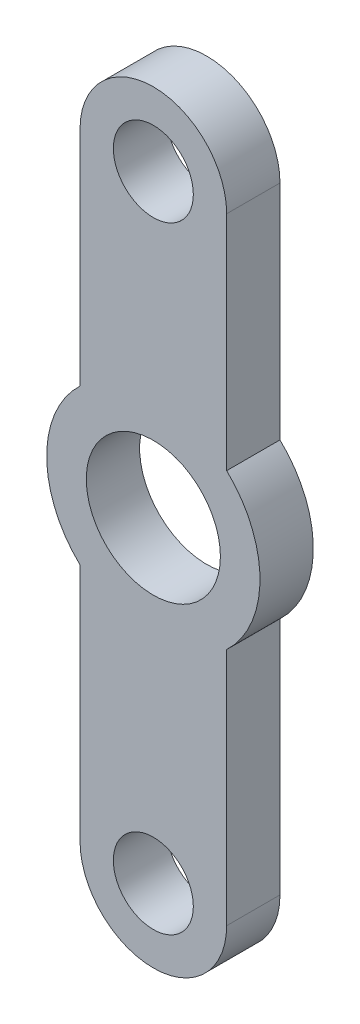
SolidWorks part; units mm, degrees
ref_plane "前视基准面" through (0, 0, 0) normal (0, 0, 1) x (1, 0, 0)
ref_plane "上视基准面" through (0, 0, 0) normal (0, 1, 0) x (1, 0, 0)
ref_plane "右视基准面" through (0, 0, 0) normal (1, 0, 0) x (0, 0, -1)
sketch "草图1" plane through (0, 0, 0) normal (0, 0, 1) x (1, 0, 0)
  line L6 (5.5, 22.5) -> (5.5, 5.8095)
  line L7 (5.5, -23.75) -> (5.5, -5.8095)
  line L8 (0, 0) -> (0, -2.2376) construction
  line L9 (-5.5, -23.75) -> (-5.5, -5.8095)
  line L10 (-5.5, 22.5) -> (-5.5, 5.8095)
  circle A0 centre (0, 0) radius 22.5 construction
  circle A1 centre (0, 0) radius 23.75 construction
  circle A2 centre (0, 22.5) radius 3
  circle A3 centre (0, -23.75) radius 3
  circle A4 centre (0, 0) radius 5.03
  circle A5 centre (0, 22.5) radius 5.5 construction
  circle A7 centre (0, -23.75) radius 5.5 construction
  arc A8 (-5.5, 22.5) -> (5.5, 22.5) centre (0, 22.5) cw
  arc A9 (-5.5, -23.75) -> (5.5, -23.75) centre (0, -23.75) ccw
  circle A12 centre (0, 0) radius 8 construction
  arc A13 (-5.5, -5.8095) -> (-5.5, 5.8095) centre (0, 0) cw
  arc A14 (5.5, 5.8095) -> (5.5, -5.8095) centre (0, 0) cw
  dimension "D1" = 6
  dimension "D2" = 45
  dimension "D3" = 47.5
  dimension "D4" = 10.06
extrude "凸台-拉伸1" add sketch "草图1" along normal blind 4
